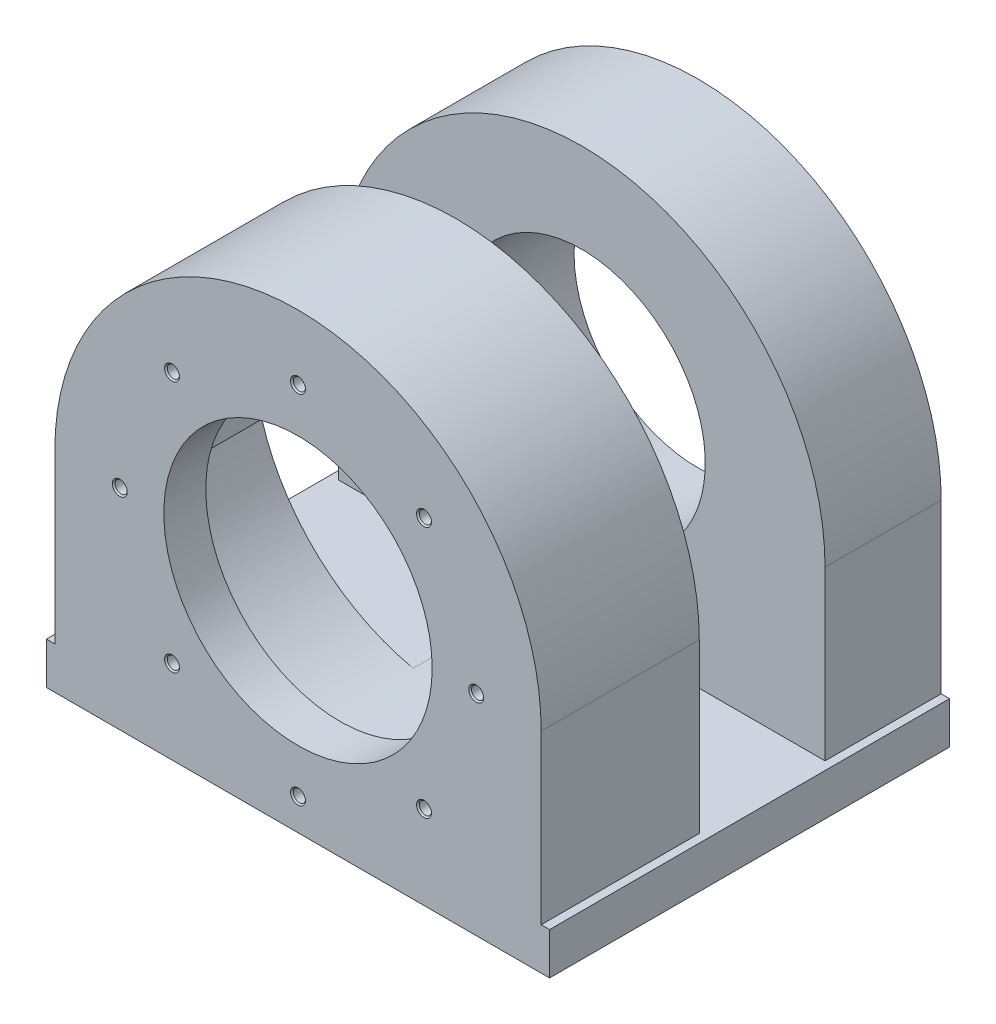
SolidWorks part; units mm, degrees
ref_plane "前视基准面" through (0, 0, 0) normal (0, 0, 1) x (1, 0, 0)
ref_plane "上视基准面" through (0, 0, 0) normal (0, 1, 0) x (1, 0, 0)
ref_plane "右视基准面" through (0, 0, 0) normal (1, 0, 0) x (0, 0, -1)
sketch "草图1" plane through (0, 0, 0) normal (0, 0, 1) x (1, 0, 0)
  line L0 (-45.6347, -2.7641) -> (74.3653, -2.7641)
  line L1 (74.3653, 7.2359) -> (72.3653, 7.2359)
  line L2 (72.3653, 7.2359) -> (72.3653, 47.2359)
  line L3 (74.3653, -2.7641) -> (74.3653, 7.2359)
  line L4 (-45.6347, -2.7641) -> (-45.6347, 7.2359)
  line L5 (-45.6347, 7.2359) -> (-43.6347, 7.2359)
  line L6 (-43.6347, 7.2359) -> (-43.6347, 47.2359)
  line L12 (-31.9477, 40.651) -> (-31.9477, 68.1464)
  line L13 (60.5523, 40.651) -> (60.5523, 68.1464)
  arc A0 (-43.6347, 47.2359) -> (72.3653, 47.2359) centre (14.3653, 47.2359) cw
  arc A3 (-31.9477, 40.651) -> (60.5523, 40.651) centre (14.3023, 54.3987) ccw
  arc A4 (60.5523, 68.1464) -> (-31.9477, 68.1464) centre (14.3023, 54.3987) ccw
  dimension "D6" = 96.5
  dimension "D1" = 120
  dimension "D2" = 2
  dimension "D3" = 40
  dimension "D5" = 10
extrude "凸台-拉伸9" add sketch "草图1" along normal blind 27.7 contours A4 L12 A3 L13 | A0 L2 L1 L3 L0 L4 L5 L6
sketch "草图8" plane through (0, 0, 0) normal (0, 0, -1) x (-1, 0, 0)
  line L0 (-74.3653, -2.7641) -> (45.6347, -2.7641)
  line L1 (45.6347, 7.2359) -> (45.6347, -2.7641)
  line L2 (-74.3653, 7.2359) -> (-74.3653, -2.7641)
  line L3 (-74.3653, 7.2359) -> (-24.4871, 7.2359)
  line L4 (45.6347, 7.2359) -> (-4.1175, 7.2359)
  arc A0 (-60.5523, 40.651) -> (31.9477, 40.651) centre (-14.3023, 54.3987) ccw construction
  arc A1 (-24.4871, 7.2359) -> (-4.1175, 7.2359) centre (-14.3023, 54.3987) ccw
extrude "凸台-拉伸10" add sketch "草图8" along normal blind 15 contours L2 L0 L1 L4 A1 L3
ref_plane "基准面5" through (0, 0, -15) normal (0, 0, -1) x (-1, 0, 0)
mirror "镜向4" about plane through (0, 0, -15) normal (0, 0, -1) of "凸台-拉伸10", "凸台-拉伸9"
sketch "草图9" plane through (0, 0, -30) normal (0, 0, -1) x (-1, 0, 0)
  line L0 (-74.3653, -2.7641) -> (45.6347, -2.7641)
  line L1 (45.6347, -2.7641) -> (45.6347, 7.2359)
  line L2 (45.6347, 7.2359) -> (-74.3653, 7.2359)
  line L3 (-74.3653, 7.2359) -> (-74.3653, -2.7641)
extrude "凸台-拉伸11" add sketch "草图9" along normal blind 27.7 contours L3 L0 L1 L2
sketch "草图10" plane through (0, 0, -57.7) normal (0, 0, -1) x (-1, 0, 0)
  line L0 (-72.3653, 7.2359) -> (-72.3653, 47.2359)
  line L1 (43.6347, 47.2359) -> (43.6347, 7.2359)
  arc A0 (-72.3653, 47.2359) -> (43.6347, 47.2359) centre (-14.3653, 47.2359) cw
  circle A1 centre (-14.3023, 54.3987) radius 29.5
  arc A2 (31.9477, 68.1464) -> (-60.5523, 68.1464) centre (-14.3023, 54.3987) ccw construction
  line M2 (45.6347, 7.2359) -> (-74.3653, 7.2359)
  dimension "D1" = 59
extrude "凸台-拉伸14" add sketch "草图10" against normal blind 27.7 contours A0 L0 L1 A1 M2
sketch "草图11" plane through (0, 0, 27.7) normal (0, 0, 1) x (1, 0, 0)
  line L0 (-45.6347, 7.2359) -> (-45.6347, -2.7641)
  line L1 (-45.6347, -2.7641) -> (74.3653, -2.7641)
  line L2 (74.3653, -2.7641) -> (74.3653, 7.2359)
  line L3 (74.3653, 7.2359) -> (72.3653, 7.2359)
  line L4 (72.3653, 7.2359) -> (72.3653, 47.2359)
  line L5 (-45.6347, 7.2359) -> (-43.6347, 7.2359)
  line L6 (-43.6347, 7.2359) -> (-43.6347, 47.2359)
  arc A0 (-43.6347, 47.2359) -> (72.3653, 47.2359) centre (14.3653, 47.2359) cw
extrude "凸台-拉伸15" add sketch "草图11" along normal blind 10
sketch "草图12" plane through (0, 0, 37.7) normal (0, 0, 1) x (1, 0, 0)
  circle A0 centre (14.3653, 47.2359) radius 32
  dimension "D1" = 64
extrude "切除-拉伸1" cut sketch "草图12" against normal blind 10 contours A0
sketch "草图21" plane through (0, 0, 37.7) normal (0, 0, 1) x (1, 0, 0)
  circle A0 centre (14.3653, 47.2359) radius 42.5
  point P4 (14.3653, 89.7359)
hole_wizard "M3.5 螺纹孔5" positions "草图21" profile "草图22" tap size "M3.5" standard "GB"
sketch "草图22" plane through (14.3653, 89.7359, 37.7) normal (1, 0, 0) x (0, -1, 0)
  line L0 (0, 0) -> (0, 10.8712)
  line L1 (0, 10.8712) -> (1.45, 10)
  line L2 (1.45, 10) -> (1.45, 0.325)
  line L3 (1.45, 0.325) -> (1.775, 0)
  line L5 (1.775, 0) -> (0, 0)
  line L6 (-1.45, 0.325) -> (-1.775, 0) construction
  line L10 (0, 10.8712) -> (-1.45, 10) construction
  line L11 (0, -6.35) -> (0, 107.95) construction
  dimension "螺纹孔钻头直径" = 2.9
  dimension "螺纹孔钻头深度" = 10
  dimension "近端锥形沉头孔直径" = 3.55
  dimension "近端锥形沉头孔角度" = 90
  dimension "导头角度" = 118
pattern_circular "阵列(圆周)1" count 8 every 45 about axis through (14.3653, 47.2359, 0) along (0, 0, 1) of "M3.5 螺纹孔5"
hole_wizard "M4 螺纹孔1" positions "草图26" profile "草图25" tap size "M4" standard "GB"
sketch "草图26" plane through (0, -2.7641, 0) normal (0, -1, 0) x (-1, 0, 0)
  point P0 (2.7382, 10)
sketch "草图25" plane through (-2.7382, -2.7641, -10) normal (1, 0, 0) x (0, 0, -1)
  line L0 (0, 0) -> (0, 2.4914)
  line L1 (0, 2.4914) -> (1.65, 1.5)
  line L2 (1.65, 1.5) -> (1.65, 0.375)
  line L3 (1.65, 0.375) -> (2.025, 0)
  line L5 (2.025, 0) -> (0, 0)
  line L6 (-1.65, 0.375) -> (-2.025, 0) construction
  line L10 (0, 2.4914) -> (-1.65, 1.5) construction
  line L11 (0, -6.35) -> (0, 107.95) construction
  dimension "螺纹孔钻头直径" = 3.3
  dimension "螺纹孔钻头深度" = 1.5
  dimension "近端锥形沉头孔直径" = 4.05
  dimension "近端锥形沉头孔角度" = 90
  dimension "导头角度" = 118
pattern_circular "阵列(圆周)2" count 6 every 60 about axis through (14.3846, 0, -10) along (0, 1, 0) of "M4 螺纹孔1"
